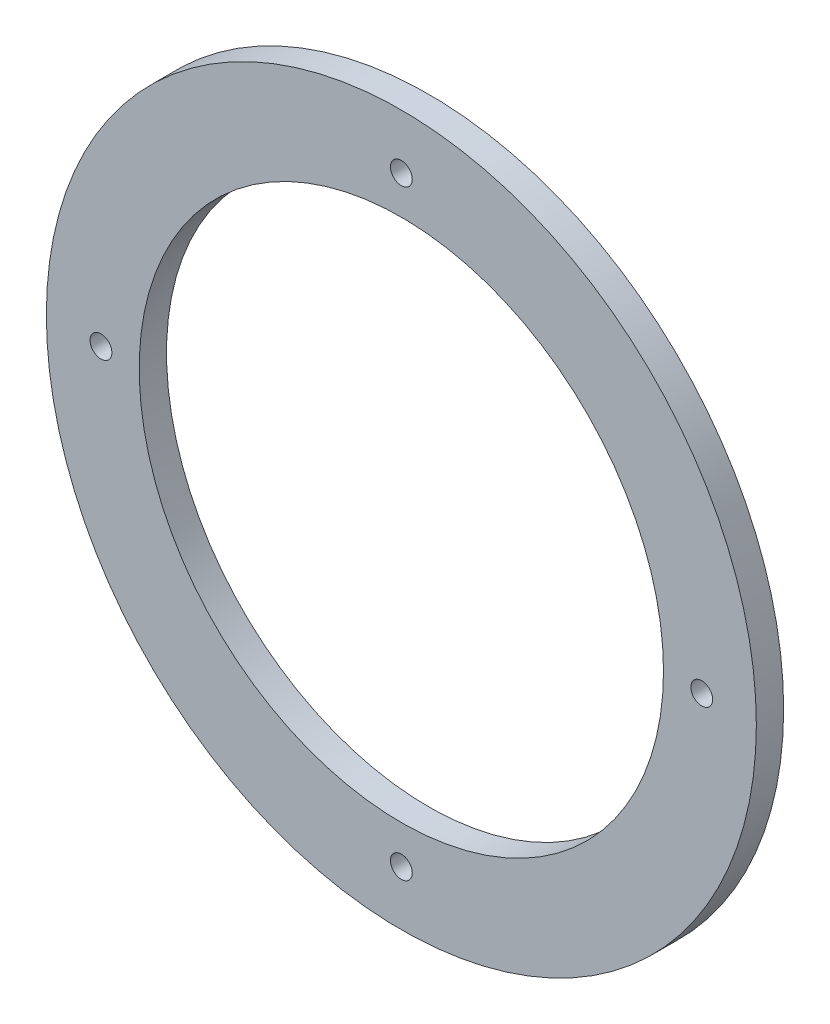
SolidWorks part; units mm, degrees
ref_plane "前视基准面" through (0, 0, 0) normal (0, 0, 1) x (1, 0, 0)
ref_plane "上视基准面" through (0, 0, 0) normal (0, 1, 0) x (1, 0, 0)
ref_plane "右视基准面" through (0, 0, 0) normal (1, 0, 0) x (0, 0, -1)
other "Configuration Table"
sketch "草图1" plane through (0, 0, 0) normal (0, 0, 1) x (1, 0, 0)
  circle A0 centre (0, 0) radius 65
  circle A1 centre (0, 0) radius 55 construction
  circle A2 centre (0, 0) radius 48
  circle A3 centre (55, 0) radius 2
  circle A4 centre (0, -55) radius 2
  circle A5 centre (-55, 0) radius 2
  circle A6 centre (0, 55) radius 2
  point P16 (0, 0)
  dimension "D1" = 130
  dimension "D2" = 96
  dimension "D3" = 110
  dimension "D4" = 4
  dimension "D5" = 4
extrude "凸台-拉伸1" add sketch "草图1" along normal blind 5
